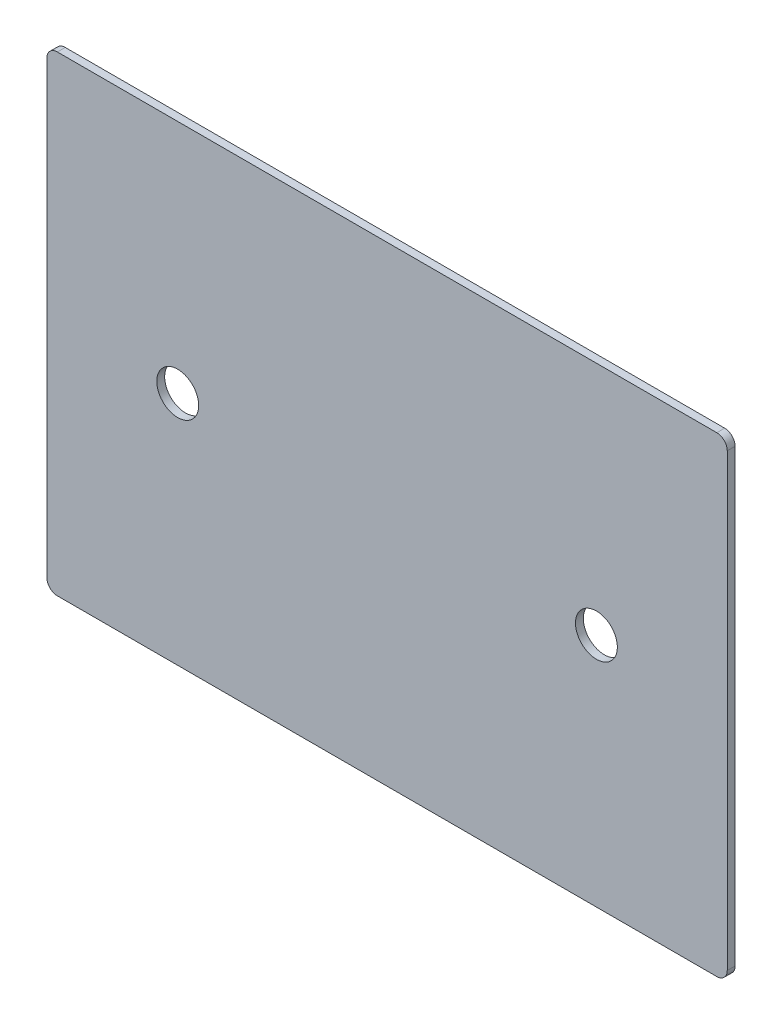
SolidWorks part; units mm, degrees
ref_plane "正面" through (0, 0, 0) normal (0, 0, 1) x (1, 0, 0)
ref_plane "平面" through (0, 0, 0) normal (0, 1, 0) x (1, 0, 0)
ref_plane "右側面" through (0, 0, 0) normal (1, 0, 0) x (0, 0, -1)
sketch "ｽｹｯﾁ1" plane through (0, 0, 0) normal (0, 0, 1) x (1, 0, 0)
  line L1 (-65, 45) -> (65, 45)
  line L2 (-65, 45) -> (-65, -45)
  line L3 (-65, -45) -> (65, -45)
  line L4 (65, 45) -> (65, -45)
  line L5 (-65, 45) -> (65, -45) construction
  line L6 (-65, -45) -> (65, 45) construction
  point P0 (0, 0)
  dimension "D1" = 90
  dimension "D2" = 130
extrude "ﾎﾞｽ - 押し出し1" add sketch "ｽｹｯﾁ1" along normal blind 1.5
sketch "ｽｹｯﾁ2" plane through (0, 0, 1.5) normal (0, 0, 1) x (1, 0, 0)
  line L0 (0, 0) -> (0, 19.7432) construction
  circle A0 centre (-40, 0) radius 4
  circle A1 centre (40, 0) radius 4
  dimension "D2" = 8
  dimension "D1" = 40
extrude "ｶｯﾄ - 押し出し1" cut sketch "ｽｹｯﾁ2" against normal blind 1.5
fillet "ﾌｨﾚｯﾄ1" radius 2 4 edges at (65, 45, 0.75) (65, -45, 0.75) (-65, -45, 0.75) (-65, 45, 0.75)
